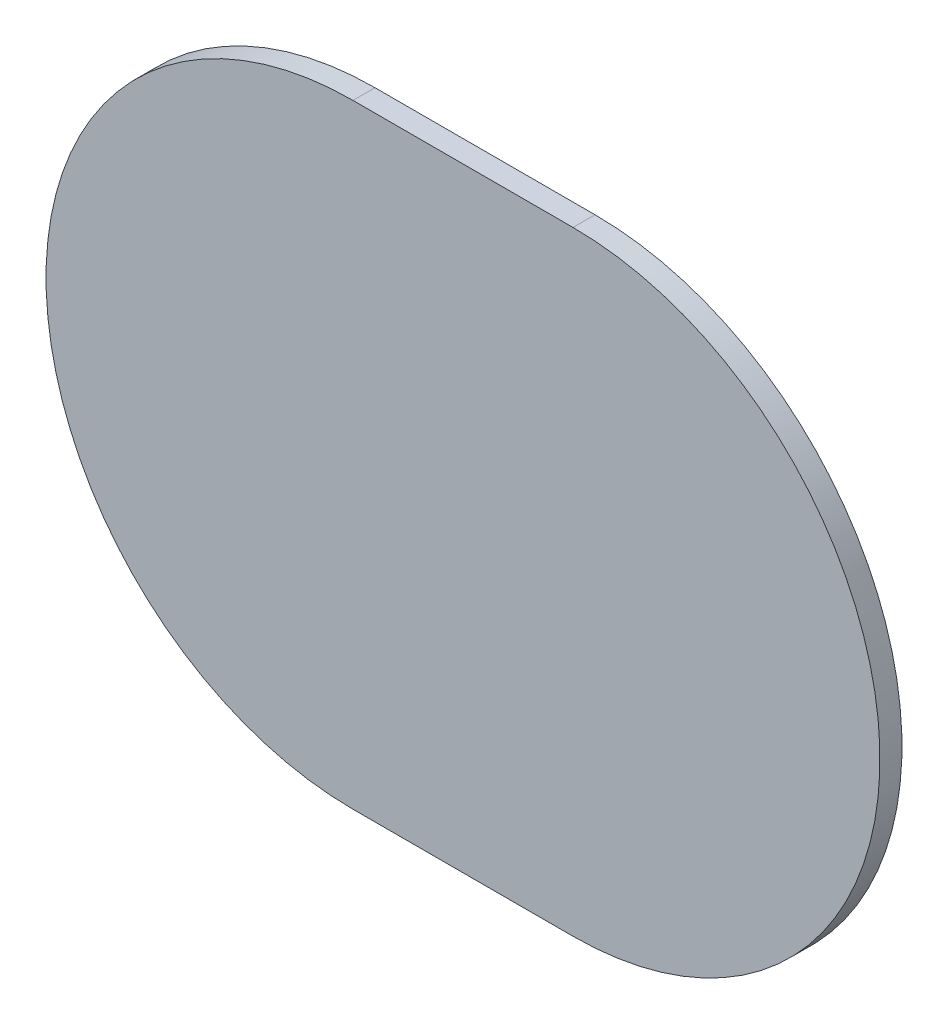
SolidWorks part; units mm, degrees
ref_plane "前视基准面" through (0, 0, 0) normal (0, 0, 1) x (1, 0, 0)
ref_plane "上视基准面" through (0, 0, 0) normal (0, 1, 0) x (1, 0, 0)
ref_plane "右视基准面" through (0, 0, 0) normal (1, 0, 0) x (0, 0, -1)
sketch "草图1" plane through (0, 0, 0) normal (0, 0, 1) x (1, 0, 0)
  line L0 (-10, -27.9) -> (10, -27.9)
  line L1 (10, 27.9) -> (-10, 27.9)
  line L2 (-10, -28) -> (10, -28)
  line L3 (10, 28) -> (-10, 28)
  line L4 (-10, -28) -> (10, -28) construction
  line L5 (10, 28) -> (-10, 28) construction
  arc A0 (10, -27.9) -> (10, 27.9) centre (10, 0) ccw
  arc A1 (-10, 27.9) -> (-10, -27.9) centre (-10, 0) ccw
  arc A2 (-10, 28) -> (-10, -28) centre (-10, 0) ccw
  arc A3 (10, -28) -> (10, 28) centre (10, 0) ccw
  arc A4 (-10, 28) -> (-10, -28) centre (-10, 0) ccw construction
  arc A5 (10, -28) -> (10, 28) centre (10, 0) ccw construction
  dimension "D1" = 0
  dimension "D2" = 0.1
extrude "凸台-拉伸1" add sketch "草图1" along normal blind 2
